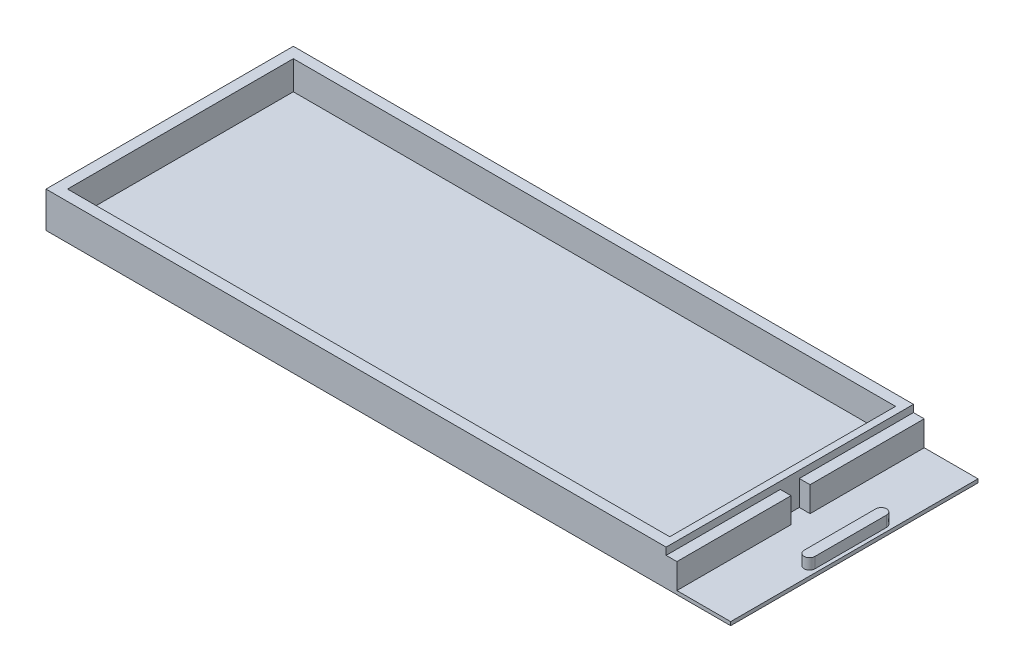
SolidWorks part; units mm, degrees
ref_plane "Front Plane" through (0, 0, 0) normal (0, 0, 1) x (1, 0, 0)
ref_plane "Top Plane" through (0, 0, 0) normal (0, 1, 0) x (1, 0, 0)
ref_plane "Right Plane" through (0, 0, 0) normal (1, 0, 0) x (0, 0, -1)
sketch "Sketch1" plane through (0, 0, 0) normal (0, 1, 0) x (1, 0, 0)
  line L0 (-84, 0) -> (-87, 0) construction
  line L1 (-84, -31.5) -> (84, -31.5)
  line L2 (-84, -31.5) -> (-84, 31.5)
  line L3 (-84, 31.5) -> (84, 31.5)
  line L4 (84, -31.5) -> (84, 31.5)
  line L5 (-84, -31.5) -> (84, 31.5) construction
  line L6 (-84, 31.5) -> (84, -31.5) construction
  line L7 (0, 31.5) -> (0, 34.5) construction
  line L8 (0, -31.5) -> (0, -34.5) construction
  line L9 (0, 34.5) -> (-87, 34.5)
  line L10 (-87, 34.5) -> (-87, -34.5)
  line L11 (-87, -34.5) -> (84, -34.5)
  line L12 (0, 34.5) -> (84, 34.5)
  line L13 (84, -34.5) -> (104, -34.5)
  line L14 (84, 34.5) -> (104, 34.5)
  line L15 (104, 34.5) -> (104, -34.5)
  point P0 (0, 0)
  dimension "D1" = 168
  dimension "D2" = 63
  dimension "D3" = 3
  dimension "D4" = 20
  dimension "D5" = 171
extrude "Boss-Extrude1" add sketch "Sketch1" along normal blind 10
sketch "Sketch2" plane through (0, 0, 0) normal (0, 1, 0) x (1, 0, 0)
  line L1 (-84, -31.5) -> (84, -31.5)
  line L2 (-84, -31.5) -> (-84, 31.5)
  line L3 (-84, 31.5) -> (84, 31.5)
  line L4 (84, -31.5) -> (84, 31.5)
  line L5 (-84, -31.5) -> (84, 31.5) construction
  line L6 (-84, 31.5) -> (84, -31.5) construction
  point P0 (0, 0)
extrude "Boss-Extrude2" add sketch "Sketch2" along normal blind 2
sketch "Sketch3" plane through (0, 10, 0) normal (0, 1, 0) x (1, 0, 0)
  line L0 (84, 31.5) -> (104, 31.5) construction
  line L1 (104, -34.5) -> (104, 34.5) construction
  line L2 (94, 31.5) -> (94, 6.5) construction
  line L3 (104, 0) -> (84, 0) construction
  line L4 (84, -31.5) -> (84, 31.5) construction
  line L5 (89, 6.5) -> (99, 6.5)
  line L6 (89, 6.5) -> (89, 31.5)
  line L7 (89, 31.5) -> (99, 31.5)
  line L8 (99, 31.5) -> (99, 6.5)
  point P14 (94, 6.5)
  dimension "D1" = 25
  dimension "D2" = 10
extrude "Cut-Extrude1" cut sketch "Sketch3" against normal through all
mirror "Mirror1" about plane through (0, 0, 0) normal (0, 0, 1) of "Cut-Extrude1"
sketch "Sketch4" plane through (0, 0, 6.5) normal (0, 0, 1) x (1, 0, 0)
  line L0 (89, 0) -> (99, 0)
  line L1 (89, 0) -> (99, 0) construction
  line L2 (94, 10) -> (94, 8) construction
  line L3 (89, 10) -> (99, 10) construction
  line L4 (99, 8) -> (89, 8)
  line L5 (89, 8) -> (89, 0)
  line L6 (99, 8) -> (99, 0)
  point P5 (94, 0)
  point P12 (94, 8)
  dimension "D1" = 10
  dimension "D2" = 2
  dimension "D3" = 8
extrude "Cut-Extrude2" cut sketch "Sketch4" against normal blind 3 and the other way up to next
mirror "Mirror2" about plane through (0, 0, 0) normal (0, 0, 1) of "Cut-Extrude2"
sketch "Sketch6" plane through (0, 0, 3.5) normal (0, 0, 1) x (1, 0, 0)
  line L0 (89, 0) -> (89, 1)
  line L1 (89, 8) -> (89, 0) construction
  line L2 (89, 1) -> (99, 1)
  line L3 (99, 8) -> (99, 0) construction
  line L4 (99, 1) -> (99, 0)
  line L5 (99, 0) -> (89, 0)
  dimension "D1" = 1
extrude "Boss-Extrude4" add sketch "Sketch6" along normal blind 31
mirror "Mirror5" about plane through (0, 0, 0) normal (0, 0, 1) of "Boss-Extrude4"
sketch "Sketch7" plane through (0, 0, 3.5) normal (0, 0, 1) x (1, 0, 0)
  line L0 (94, 8) -> (94, 1) construction
  line L1 (89, 8) -> (99, 8) construction
  line L2 (99, 1) -> (89, 1) construction
  circle A0 centre (94, 4.5) radius 1.5
  dimension "D1" = 3
extrude "Boss-Extrude5" add sketch "Sketch7" along normal blind 3
mirror "Mirror6" about plane through (0, 0, 0) normal (0, 0, 1) of "Boss-Extrude5"
sketch "Sketch8" plane through (-87, 0, 0) normal (-1, 0, 0) x (0, 0, 1)
  line L0 (5, 0) -> (-5, 0)
  line L1 (-34.5, 0) -> (34.5, 0) construction
  line L2 (-5, 0) -> (-5, 5)
  line L3 (-5, 5) -> (5, 5)
  line L4 (5, 5) -> (5, 0)
  point P6 (0, 0)
  dimension "D1" = 10
  dimension "D2" = 5
extrude "Boss-Extrude6" add sketch "Sketch8" along normal blind 3
sketch "Sketch9" plane through (0, 0, 34.5) normal (0, 0, 1) x (1, 0, 0)
  line L0 (-87, 0) -> (104, 0) construction
  line L1 (104, 10) -> (89, 10)
  line L2 (104, 10) -> (104, 0)
  line L3 (104, 0) -> (89, 0)
  line L4 (89, 10) -> (89, 0)
  dimension "D1" = 15
extrude "Cut-Extrude3" cut sketch "Sketch9" against normal through all
sketch "Sketch10" plane through (89, 0, 0) normal (1, 0, 0) x (0, 0, -1)
  line L0 (-34.5, 0) -> (-34.5, 1)
  line L1 (-34.5, 0) -> (-34.5, 10) construction
  line L2 (-34.5, 1) -> (34.5, 1)
  line L3 (34.5, 0) -> (34.5, 10) construction
  line L4 (34.5, 1) -> (34.5, 0)
  line L5 (34.5, 0) -> (-34.5, 0)
  dimension "D1" = 1
extrude "Boss-Extrude7" add sketch "Sketch10" along normal blind 15
sketch "Sketch12" plane through (0, 0, 34.5) normal (0, 0, 1) x (1, 0, 0)
  line L1 (89, 10) -> (86, 10)
  line L2 (89, 10) -> (89, 8)
  line L3 (89, 8) -> (86, 8)
  line L4 (86, 10) -> (86, 8)
  dimension "D1" = 2
  dimension "D2" = 3
extrude "Cut-Extrude5" cut sketch "Sketch12" against normal through all
sketch "Sketch13" plane through (89, 0, 0) normal (1, 0, 0) x (0, 0, -1)
  line L0 (0, 8) -> (0, 1) construction
  line L1 (34.5, 8) -> (-34.5, 8) construction
  line L2 (34.5, 1) -> (-34.5, 1) construction
  line L3 (-2.65, 8) -> (2.65, 8)
  line L4 (34.5, 8) -> (-34.5, 8) construction
  line L5 (-2.65, 8) -> (-2.65, 1)
  line L6 (34.5, 1) -> (-34.5, 1) construction
  line L7 (-2.65, 1) -> (2.65, 1)
  line L8 (2.65, 1) -> (2.65, 8)
  point P11 (0, 8)
  dimension "D1" = 5.3
extrude "Cut-Extrude6" cut sketch "Sketch13" against normal blind 3
sketch "Sketch15" plane through (0, 1, 0) normal (0, 1, 0) x (1, 0, 0)
  line L0 (104, 0) -> (101.5, 0) construction
  line L1 (104, 34.5) -> (104, -34.5) construction
  line L2 (101.5, -10) -> (101.5, 10) construction
  line L3 (101.5, 10) -> (101.5, -10) construction
  line L4 (103, 10) -> (103, -10)
  line L5 (100, 10) -> (100, -10)
  arc A0 (103, 10) -> (100, 10) centre (101.5, 10) ccw
  arc A1 (100, -10) -> (103, -10) centre (101.5, -10) ccw
  point P5 (101.5, 0)
  point P8 (101.5, 0)
  dimension "D1" = 2.5
  dimension "D2" = 20
  dimension "D3" = 3
extrude "Boss-Extrude8" add sketch "Sketch15" along normal blind 3
